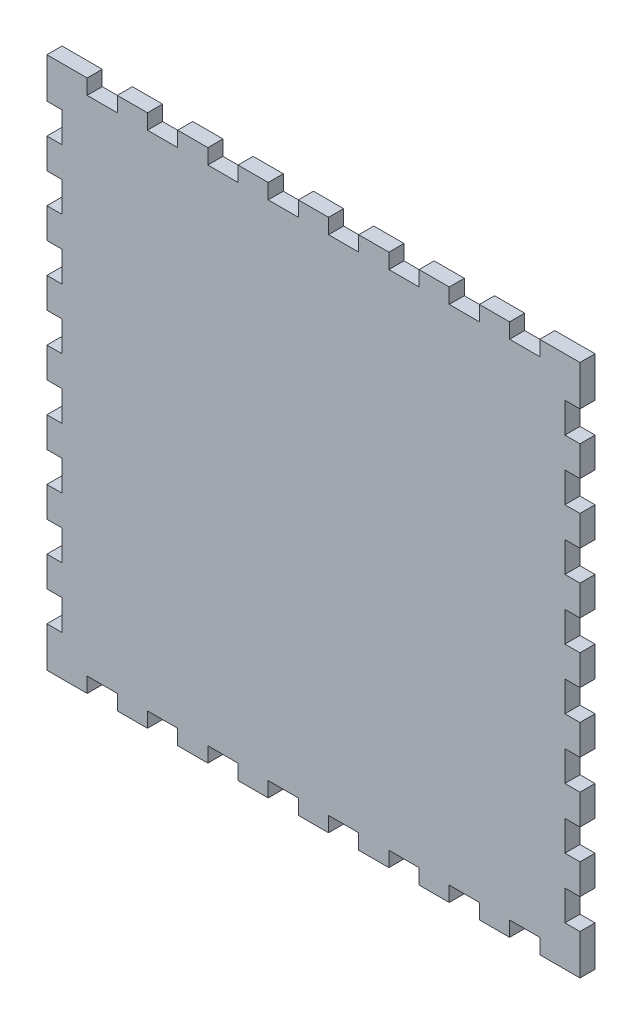
SolidWorks part; units mm, degrees
ref_plane "Front Plane" through (0, 0, 0) normal (0, 0, 1) x (1, 0, 0)
ref_plane "Top Plane" through (0, 0, 0) normal (0, 1, 0) x (1, 0, 0)
ref_plane "Right Plane" through (0, 0, 0) normal (1, 0, 0) x (0, 0, -1)
sketch "Model" plane through (0, 0, 0) normal (0, 0, 1) x (1, 0, 0)
  line L0 (0, 215) -> (0, 199)
  line L1 (0, 199) -> (6, 199)
  line L2 (6, 199) -> (6, 187)
  line L3 (6, 187) -> (0, 187)
  line L4 (0, 187) -> (0, 175)
  line L5 (0, 175) -> (6, 175)
  line L6 (6, 175) -> (6, 163)
  line L7 (6, 163) -> (0, 163)
  line L8 (0, 163) -> (0, 151)
  line L9 (0, 151) -> (6, 151)
  line L10 (6, 151) -> (6, 139)
  line L11 (6, 139) -> (0, 139)
  line L12 (0, 139) -> (0, 127)
  line L13 (0, 127) -> (6, 127)
  line L14 (6, 127) -> (6, 115)
  line L15 (6, 115) -> (0, 115)
  line L16 (0, 115) -> (0, 103)
  line L17 (0, 103) -> (6, 103)
  line L18 (6, 103) -> (6, 91)
  line L19 (6, 91) -> (0, 91)
  line L20 (0, 91) -> (0, 79)
  line L21 (0, 79) -> (6, 79)
  line L22 (6, 79) -> (6, 67)
  line L23 (6, 67) -> (0, 67)
  line L24 (0, 67) -> (0, 55)
  line L25 (0, 55) -> (6, 55)
  line L26 (6, 55) -> (6, 43)
  line L27 (6, 43) -> (0, 43)
  line L28 (0, 43) -> (0, 31)
  line L29 (0, 31) -> (6, 31)
  line L30 (6, 31) -> (6, 19)
  line L31 (6, 19) -> (0, 19)
  line L32 (0, 19) -> (0, 3)
  line L33 (0, 3) -> (16, 3)
  line L34 (16, 3) -> (16, 9)
  line L35 (16, 9) -> (28, 9)
  line L36 (28, 9) -> (28, 3)
  line L37 (28, 3) -> (40, 3)
  line L38 (40, 3) -> (40, 9)
  line L39 (40, 9) -> (52, 9)
  line L40 (52, 9) -> (52, 3)
  line L41 (52, 3) -> (64, 3)
  line L42 (64, 3) -> (64, 9)
  line L43 (64, 9) -> (76, 9)
  line L44 (76, 9) -> (76, 3)
  line L45 (76, 3) -> (88, 3)
  line L46 (88, 3) -> (88, 9)
  line L47 (88, 9) -> (100, 9)
  line L48 (100, 9) -> (100, 3)
  line L49 (100, 3) -> (112, 3)
  line L50 (112, 3) -> (112, 9)
  line L51 (112, 9) -> (124, 9)
  line L52 (124, 9) -> (124, 3)
  line L53 (124, 3) -> (136, 3)
  line L54 (136, 3) -> (136, 9)
  line L55 (136, 9) -> (148, 9)
  line L56 (148, 9) -> (148, 3)
  line L57 (148, 3) -> (160, 3)
  line L58 (160, 3) -> (160, 9)
  line L59 (160, 9) -> (172, 9)
  line L60 (172, 9) -> (172, 3)
  line L61 (172, 3) -> (184, 3)
  line L62 (184, 3) -> (184, 9)
  line L63 (184, 9) -> (196, 9)
  line L64 (196, 9) -> (196, 3)
  line L65 (196, 3) -> (212, 3)
  line L66 (212, 3) -> (212, 19)
  line L67 (212, 19) -> (206, 19)
  line L68 (206, 19) -> (206, 31)
  line L69 (206, 31) -> (212, 31)
  line L70 (212, 31) -> (212, 43)
  line L71 (212, 43) -> (206, 43)
  line L72 (206, 43) -> (206, 55)
  line L73 (206, 55) -> (212, 55)
  line L74 (212, 55) -> (212, 67)
  line L75 (212, 67) -> (206, 67)
  line L76 (206, 67) -> (206, 79)
  line L77 (206, 79) -> (212, 79)
  line L78 (212, 79) -> (212, 91)
  line L79 (212, 91) -> (206, 91)
  line L80 (206, 91) -> (206, 103)
  line L81 (206, 103) -> (212, 103)
  line L82 (212, 103) -> (212, 115)
  line L83 (212, 115) -> (206, 115)
  line L84 (206, 115) -> (206, 127)
  line L85 (206, 127) -> (212, 127)
  line L86 (212, 127) -> (212, 139)
  line L87 (212, 139) -> (206, 139)
  line L88 (206, 139) -> (206, 151)
  line L89 (206, 151) -> (212, 151)
  line L90 (212, 151) -> (212, 163)
  line L91 (212, 163) -> (206, 163)
  line L92 (206, 163) -> (206, 175)
  line L93 (206, 175) -> (212, 175)
  line L94 (212, 175) -> (212, 187)
  line L95 (212, 187) -> (206, 187)
  line L96 (206, 187) -> (206, 199)
  line L97 (206, 199) -> (212, 199)
  line L98 (212, 199) -> (212, 215)
  line L99 (212, 215) -> (196, 215)
  line L100 (196, 215) -> (196, 209)
  line L101 (196, 209) -> (184, 209)
  line L102 (184, 209) -> (184, 215)
  line L103 (184, 215) -> (172, 215)
  line L104 (172, 215) -> (172, 209)
  line L105 (172, 209) -> (160, 209)
  line L106 (160, 209) -> (160, 215)
  line L107 (160, 215) -> (148, 215)
  line L108 (148, 215) -> (148, 209)
  line L109 (148, 209) -> (136, 209)
  line L110 (136, 209) -> (136, 215)
  line L111 (136, 215) -> (124, 215)
  line L112 (124, 215) -> (124, 209)
  line L113 (124, 209) -> (112, 209)
  line L114 (112, 209) -> (112, 215)
  line L115 (112, 215) -> (100, 215)
  line L116 (100, 215) -> (100, 209)
  line L117 (100, 209) -> (88, 209)
  line L118 (88, 209) -> (88, 215)
  line L119 (88, 215) -> (76, 215)
  line L120 (76, 215) -> (76, 209)
  line L121 (76, 209) -> (64, 209)
  line L122 (64, 209) -> (64, 215)
  line L123 (64, 215) -> (52, 215)
  line L124 (52, 215) -> (52, 209)
  line L125 (52, 209) -> (40, 209)
  line L126 (40, 209) -> (40, 215)
  line L127 (40, 215) -> (28, 215)
  line L128 (28, 215) -> (28, 209)
  line L129 (28, 209) -> (16, 209)
  line L130 (16, 209) -> (16, 215)
  line L131 (16, 215) -> (0, 215)
extrude "Boss-Extrude1" add sketch "Model" along normal blind 6
